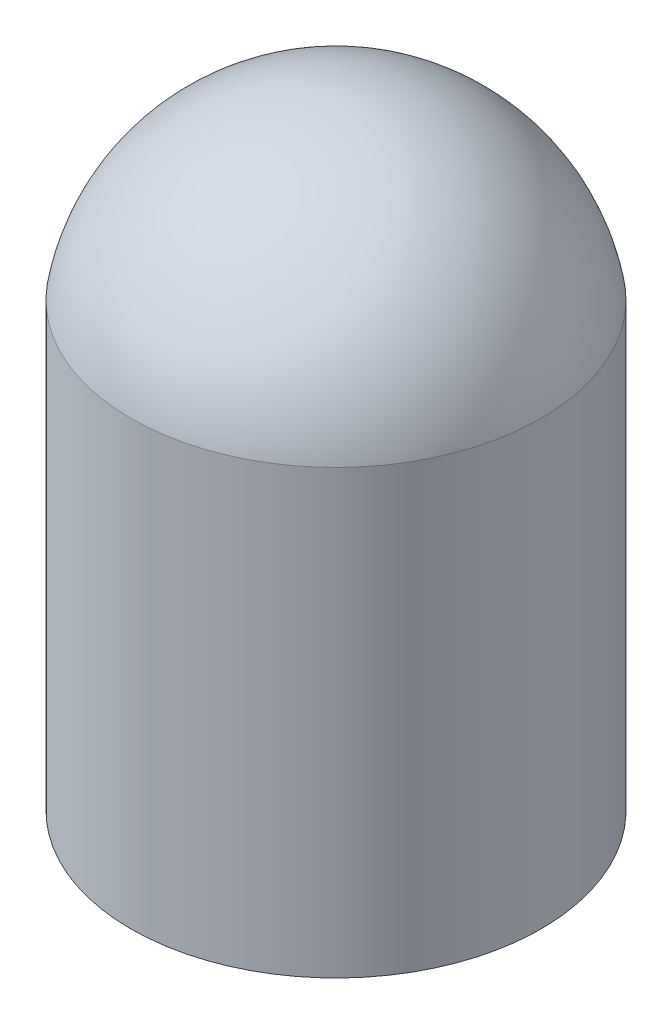
SolidWorks part; units mm, degrees
ref_plane "Спереди" through (0, 0, 0) normal (0, 0, 1) x (1, 0, 0)
ref_plane "Сверху" through (0, 0, 0) normal (0, 1, 0) x (1, 0, 0)
ref_plane "Справа" through (0, 0, 0) normal (1, 0, 0) x (0, 0, -1)
sketch "Эскиз1" plane through (0, 0, 0) normal (1, 0, 0) x (0, 0, -1)
  line L0 (-88.0069, -25.6158) -> (-88.0069, -36.3958)
  line L1 (-88.0069, -36.3958) -> (-83.0071, -36.3958)
  line L3 (-83.0071, -36.3958) -> (-83.0071, -21.3958)
  arc A0 (-88.0069, -25.6158) -> (-83.0071, -21.3958) centre (-83.0134, -26.4602) cw
  dimension "D1" = 15
  dimension "D2" = 4.9998
revolve "Повернуть1" add sketch "Эскиз1" angle 360 about L3
